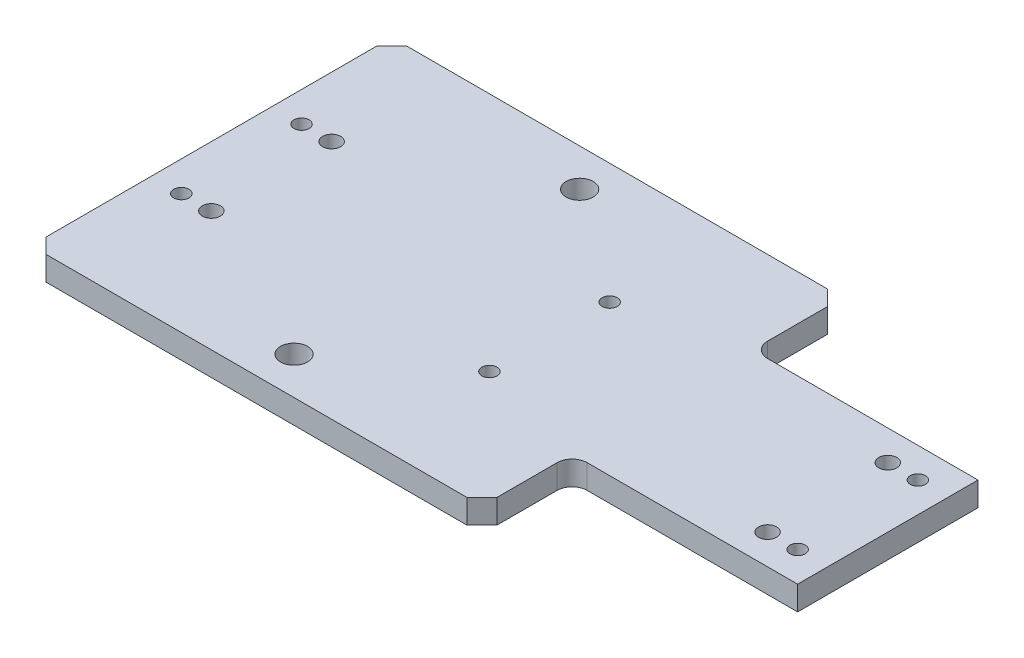
SolidWorks part; units mm, degrees
ref_plane "正面" through (0, 0, 0) normal (0, 0, 1) x (1, 0, 0)
ref_plane "平面" through (0, 0, 0) normal (0, 1, 0) x (1, 0, 0)
ref_plane "右側面" through (0, 0, 0) normal (1, 0, 0) x (0, 0, -1)
sketch "ｽｹｯﾁ1" plane through (0, 0, 0) normal (0, 1, 0) x (1, 0, 0)
  line L0 (-215, -120) -> (65, -120)
  line L1 (65, -120) -> (75, -110)
  line L2 (75, -110) -> (75, -70)
  line L3 (85, -60) -> (225, -60)
  line L4 (225, -60) -> (225, 60)
  line L5 (225, 60) -> (85, 60)
  line L6 (75, 70) -> (75, 110)
  line L7 (75, 110) -> (65, 120)
  line L8 (65, 120) -> (-215, 120)
  line L9 (-215, 120) -> (-225, 110)
  line L10 (-225, 110) -> (-225, -110)
  line L11 (-225, -110) -> (-215, -120)
  arc A0 (75, -70) -> (85, -60) centre (85, -70) cw
  arc A1 (85, 60) -> (75, 70) centre (85, 70) cw
extrude "ﾎﾞｽ - 押し出し1" add sketch "ｽｹｯﾁ1" along normal blind 16
sketch "ｽｹｯﾁ2" plane through (0, 0, 0) normal (0, 1, 0) x (1, 0, 0)
  circle A0 centre (-75, -95) radius 9
  circle A1 centre (-75, 95) radius 9
extrude "ｶｯﾄ - 押し出し1" cut sketch "ｽｹｯﾁ2" against normal through all and the other way through all
sketch "ｽｹｯﾁ3" plane through (0, 0, 0) normal (0, 1, 0) x (1, 0, 0)
  circle A0 centre (-185, -40) radius 6
  circle A1 centre (-185, 40) radius 6
  circle A2 centre (185, -40) radius 6
  circle A3 centre (185, 40) radius 6
extrude "ｶｯﾄ - 押し出し2" cut sketch "ｽｹｯﾁ3" against normal through all and the other way through all
sketch "ｽｹｯﾁ4" plane through (0, 0, 0) normal (0, 1, 0) x (1, 0, 0)
  circle A0 centre (-205, -40) radius 5.053
  circle A1 centre (-205, 40) radius 5.053
  circle A2 centre (0, -40) radius 5.053
  circle A3 centre (0, 40) radius 5.053
  circle A4 centre (205, -40) radius 5.053
  circle A5 centre (205, 40) radius 5.053
extrude "ｶｯﾄ - 押し出し3" cut sketch "ｽｹｯﾁ4" against normal through all and the other way through all
